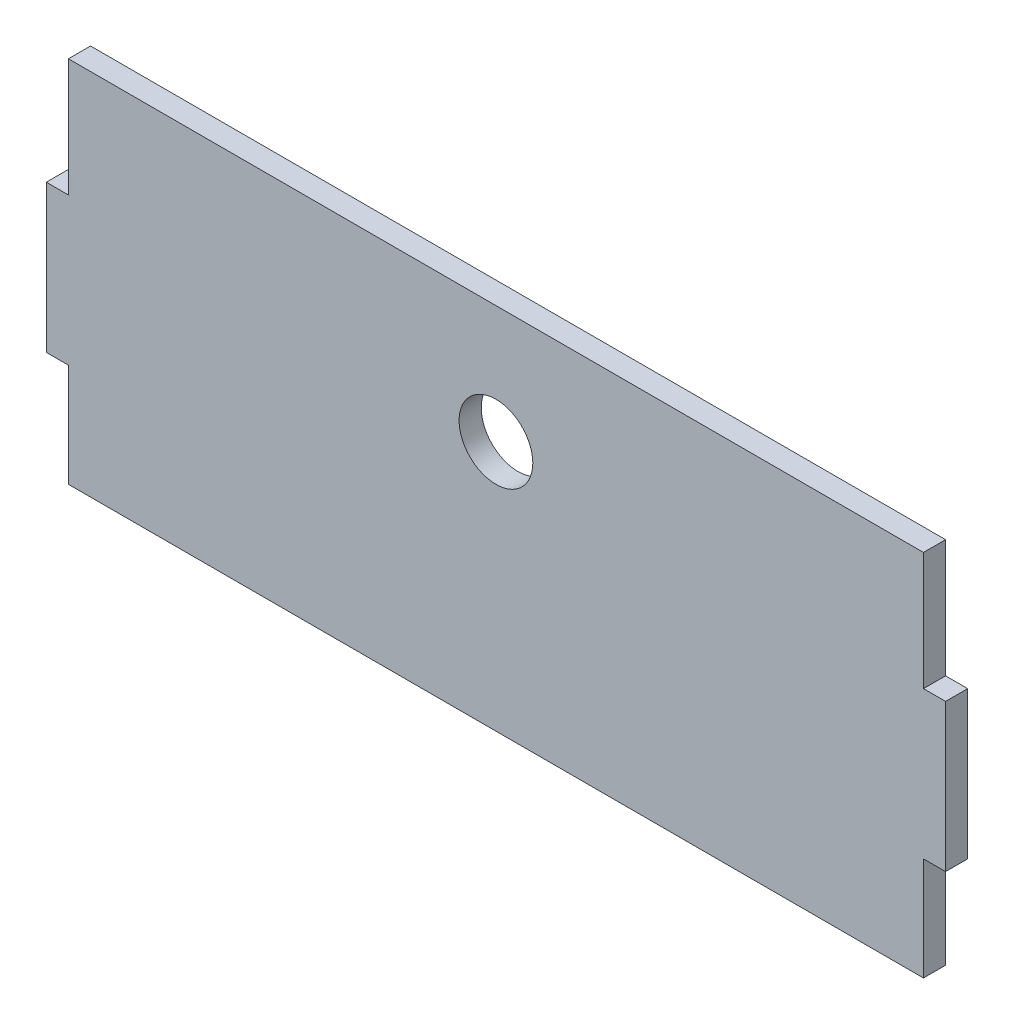
SolidWorks part; units mm, degrees
material "Acrylic (Medium-high impact)"
ref_plane "Front Plane" through (0, 0, 0) normal (0, 0, 1) x (1, 0, 0)
ref_plane "Top Plane" through (0, 0, 0) normal (0, 1, 0) x (1, 0, 0)
ref_plane "Right Plane" through (0, 0, 0) normal (1, 0, 0) x (0, 0, -1)
sketch "Sketch1" plane through (0, 0, 0) normal (0, 0, 1) x (1, 0, 0)
  line L0 (-61, 10) -> (-61, -10)
  line L1 (-61, -10) -> (-58, -10)
  line L2 (-58, -10) -> (-58, -24)
  line L3 (-58, -24) -> (58, -24)
  line L4 (58, -24) -> (58, -10)
  line L5 (58, -10) -> (61, -10)
  line L6 (61, -10) -> (61, 10)
  line L7 (61, 10) -> (58, 10)
  line L8 (58, 10) -> (58, 26)
  line L9 (58, 26) -> (-58, 26)
  line L10 (-58, 26) -> (-58, 10)
  line L11 (-58, 10) -> (-61, 10)
  line L12 (-61, 0) -> (0, 0) construction
  line L13 (0, 0) -> (61, 0) construction
  circle A0 centre (0, 10) radius 5
  dimension "D6" = 10
  dimension "D1" = 3
  dimension "D2" = 20
  dimension "D3" = 50
  dimension "D4" = 116
  dimension "D5" = 14
extrude "Boss-Extrude1" add sketch "Sketch1" along normal blind 3
